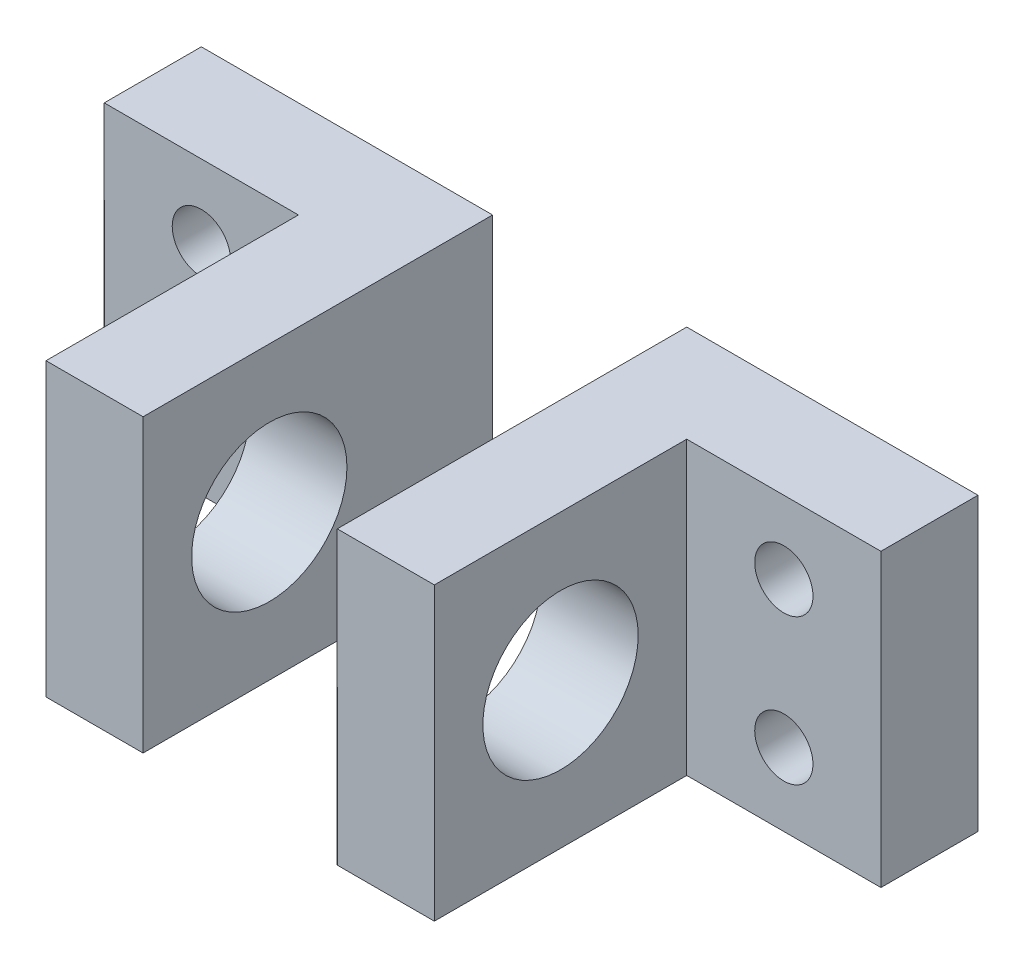
SolidWorks part; units mm, degrees
ref_plane "Front Plane" through (0, 0, 0) normal (0, 0, 1) x (1, 0, 0)
ref_plane "Top Plane" through (0, 0, 0) normal (0, 1, 0) x (1, 0, 0)
ref_plane "Right Plane" through (0, 0, 0) normal (1, 0, 0) x (0, 0, -1)
sketch "Sketch1" plane through (0, 0, 0) normal (0, 1, 0) x (1, 0, 0)
  line L0 (0, 0) -> (0, 22.4056) construction
  line L5 (-5, 18) -> (-5, 0)
  line L6 (-5, 0) -> (-10, 0)
  line L7 (-10, 0) -> (-10, 13)
  line L8 (-10, 13) -> (-20, 13)
  line L9 (-20, 13) -> (-20, 18)
  line L10 (-20, 18) -> (-5, 18)
  line L11 (20, 18) -> (5, 18)
  line L12 (20, 13) -> (20, 18)
  line L13 (10, 13) -> (20, 13)
  line L14 (10, 0) -> (10, 13)
  line L15 (5, 0) -> (10, 0)
  line L16 (5, 18) -> (5, 0)
  dimension "D1" = 5
  dimension "D2" = 5
  dimension "D3" = 15
  dimension "D4" = 18
  dimension "D5" = 5
extrude "Boss-Extrude1" add sketch "Sketch1" along normal blind 15
sketch "Sketch2" plane through (10, 0, 0) normal (1, 0, 0) x (0, 0, -1)
  line L0 (0, 0) -> (13, 15) construction
  circle A0 centre (6.5, 7.5) radius 4
  dimension "D1" = 8
extrude "Cut-Extrude1" cut sketch "Sketch2" against normal through all
sketch "Sketch3" plane through (0, 0, -13) normal (0, 0, 1) x (1, 0, 0)
  line L0 (-15, 15) -> (-15, 0) construction
  line L1 (-20, 15) -> (-10, 15) construction
  line L2 (-20, 0) -> (-10, 0) construction
  line L3 (-20, 7.5) -> (-10, 7.5) construction
  line L4 (-20, 15) -> (-20, 0) construction
  line L5 (-10, 15) -> (-10, 0) construction
  line L6 (-20, 7.5) -> (-10, 15) construction
  line L7 (-20, 7.5) -> (-10, 0) construction
  line L8 (0, 0) -> (0, 15.6669) construction
  circle A0 centre (-15, 3.75) radius 1.5
  circle A1 centre (-15, 11.25) radius 1.5
  circle A2 centre (15, 11.25) radius 1.5
  circle A3 centre (15, 3.75) radius 1.5
  dimension "D1" = 3
extrude "Cut-Extrude2" cut sketch "Sketch3" against normal through all
sketch "Sketch4" plane through (10, 0, 0) normal (1, 0, 0) x (0, 0, -1)
  line L0 (0, 7.5) -> (13, 7.5) construction
  line L1 (0, 15) -> (0, 0) construction
  line L2 (13, 15) -> (13, 0) construction
sketch "Sketch5" plane through (-10, 0, 0) normal (-1, 0, 0) x (0, 0, 1)
  line L0 (-13, 7.5) -> (0, 7.5) construction
  line L1 (-13, 15) -> (-13, 0) construction
  line L2 (0, 15) -> (0, 0) construction
sketch "Sketch6" plane through (0, 0, 0) normal (0, 0, 1) x (1, 0, 0)
  line L0 (-10, 7.5) -> (10, 7.5) construction
  line L1 (-10, 15) -> (-10, 0) construction
